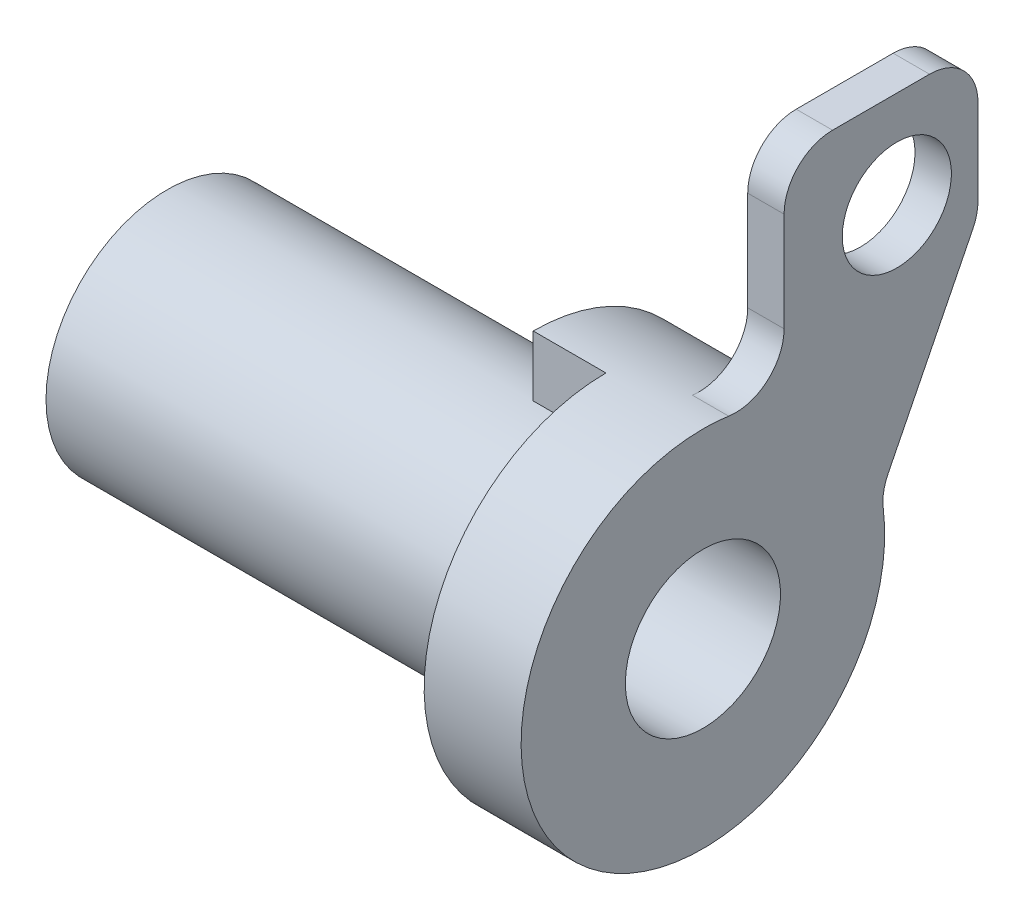
SolidWorks part; units mm, degrees
material "PLA"
ref_plane "Front" through (0, 0, 0) normal (0, 0, 1) x (1, 0, 0)
ref_plane "Top" through (0, 0, 0) normal (0, 1, 0) x (1, 0, 0)
ref_plane "Right" through (0, 0, 0) normal (1, 0, 0) x (0, 0, -1)
sketch "Skizze1" plane through (0, 0, 0) normal (0, 0, 1) x (1, 0, 0)
  line L0 (0, 0) -> (45.0977, 0) construction
  line L1 (0, 7.5) -> (22.1, 7.5)
  line L2 (0, 7.5) -> (0, 3.2)
  line L3 (0, 3.2) -> (22.1, 3.2)
  line L4 (22.1, 7.5) -> (22.1, 3.2)
  dimension "D1" = 15
  dimension "D2" = 6.4
  dimension "23" = 22.1
revolve "Rotation1" add sketch "Skizze1" angle 360 about L0
sketch "Skizze2" plane through (0, 0, 0) normal (-1, 0, 0) x (0, 0, 1)
  circle A6 centre (0, 0) radius 5
  circle A7 centre (0, 0) radius 7.5 construction
  circle A8 centre (0, 0) radius 7.5
  dimension "D2" = 10
extrude "Schnitt-Linear austragen2" cut sketch "Skizze2" against normal offset from surface (15.1 mm away) 7 up to face at (22.1, 0, 7.5)
sketch "Skizze3" plane through (15.1, 0, 0) normal (-1, 0, 0) x (0, 0, 1)
  line L0 (0, 5) -> (0, 7.5)
  line L1 (0, 0) -> (0.6526, -4.9572) construction
  line L2 (0, -8.3139) -> (0, 2.0709) construction
  line L3 (0.6526, -4.9572) -> (-1.6959, -7.3057)
  circle A0 centre (0, 0) radius 7.5 construction
  circle A1 centre (0, 0) radius 5 construction
  arc A2 (-1.6959, -7.3057) -> (0, 7.5) centre (0, 0) ccw
  arc A3 (0.6526, -4.9572) -> (0, 5) centre (0, 0) ccw
  dimension "D1" = 7.5
  dimension "D2" = 45
extrude "Schnitt-Linear austragen4" cut sketch "Skizze3" against normal blind 3
sketch "Skizze4" plane through (22.1, 0, 0) normal (1, 0, 0) x (0, 0, -1)
  line L0 (3.3485, 6.711) -> (3.3485, 15.5)
  line L4 (11.3485, 9.5) -> (11.3485, 15.5)
  line L5 (11.3485, 15.5) -> (3.3485, 15.5)
  line L6 (7.3485, 1.5) -> (11.3485, 9.5)
  circle A0 centre (0, 0) radius 7.5 construction
  arc A1 (7.3485, 1.5) -> (3.3485, 6.711) centre (0, 0) ccw
  dimension "D1" = 8
  dimension "D2" = 4
  dimension "D3" = 6
  dimension "D4" = 8
  dimension "D5" = 8
extrude "Aufsatz-Linear austragen1" add sketch "Skizze4" against normal blind 1.5
hole_wizard "Durchgangsloch für M41" positions "Skizze5" profile "Skizze6" hole size "M4" standard "DIN" end condition through all
sketch "Skizze5" plane through (18.1, 0, 0) normal (-1, 0, 0) x (0, 0, 1)
  line L6 (-11.3485, 15.5) -> (-3.3485, 15.5) construction
  point P0 (-8, 11.5)
  dimension "D1" = 8
  dimension "D2" = 4
sketch "Skizze6" plane through (18.1, 11.5, -8) normal (0, 1, 0) x (0, 0, 1)
  line L0 (0, 0) -> (0, 4)
  line L1 (0, 4) -> (2.25, 4)
  line L2 (2.25, 4) -> (2.25, 0)
  line L5 (2.25, 0) -> (0, 0)
  line L11 (0, -6.35) -> (0, 107.95) construction
  dimension "Bohrerdurchmesser" = 4.5
  dimension "Bohrungstiefe" = 4
fillet "Verrundung3" radius 2 5 edges at (21.35, 1.5, -7.3485) (21.35, 9.5, -11.3485) (21.35, 15.5, -11.3485) (21.35, 15.5, -3.3485) (21.35, 6.711, -3.3485)
